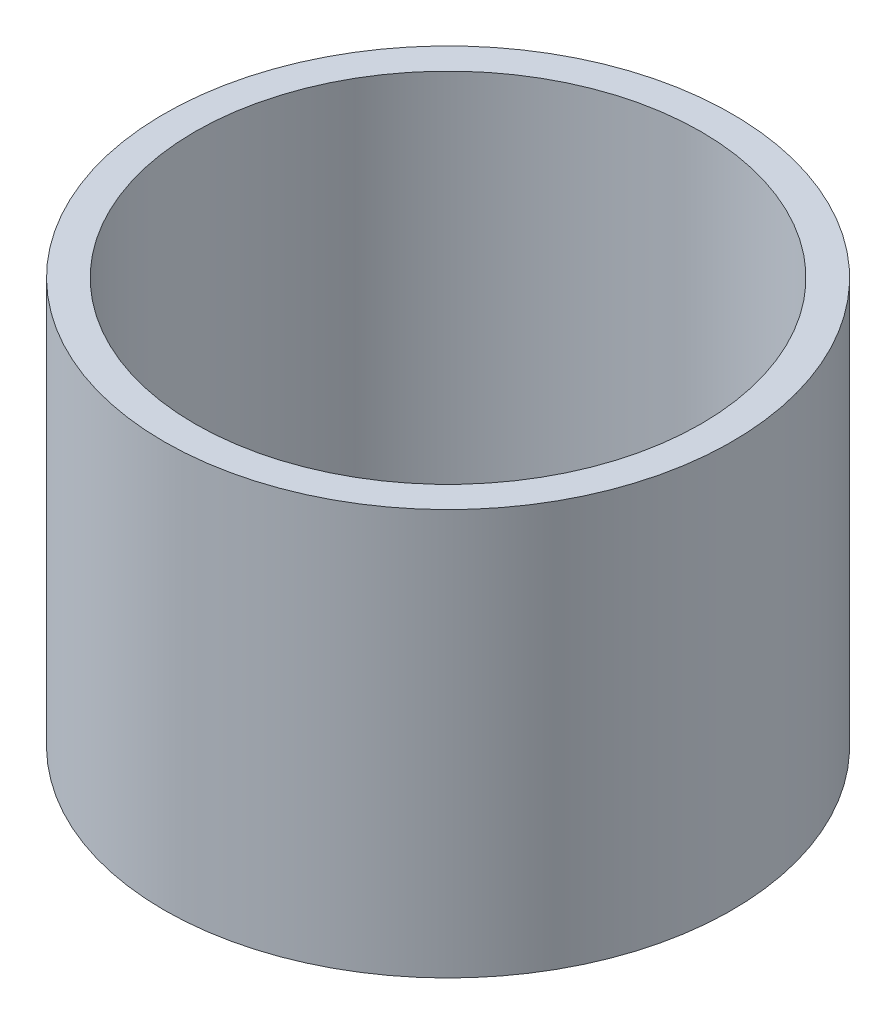
SolidWorks part; units mm, degrees
ref_plane "Front Plane" through (0, 0, 0) normal (0, 0, 1) x (1, 0, 0)
ref_plane "Top Plane" through (0, 0, 0) normal (0, 1, 0) x (1, 0, 0)
ref_plane "Right Plane" through (0, 0, 0) normal (1, 0, 0) x (0, 0, -1)
sketch "Sketch1" plane through (0, 0, 0) normal (0, 1, 0) x (1, 0, 0)
  circle A0 centre (0, 0) radius 14
  circle A1 centre (0, 0) radius 12.4777
  dimension "D1" = 28
extrude "Boss-Extrude1" add sketch "Sketch1" along normal blind 20
